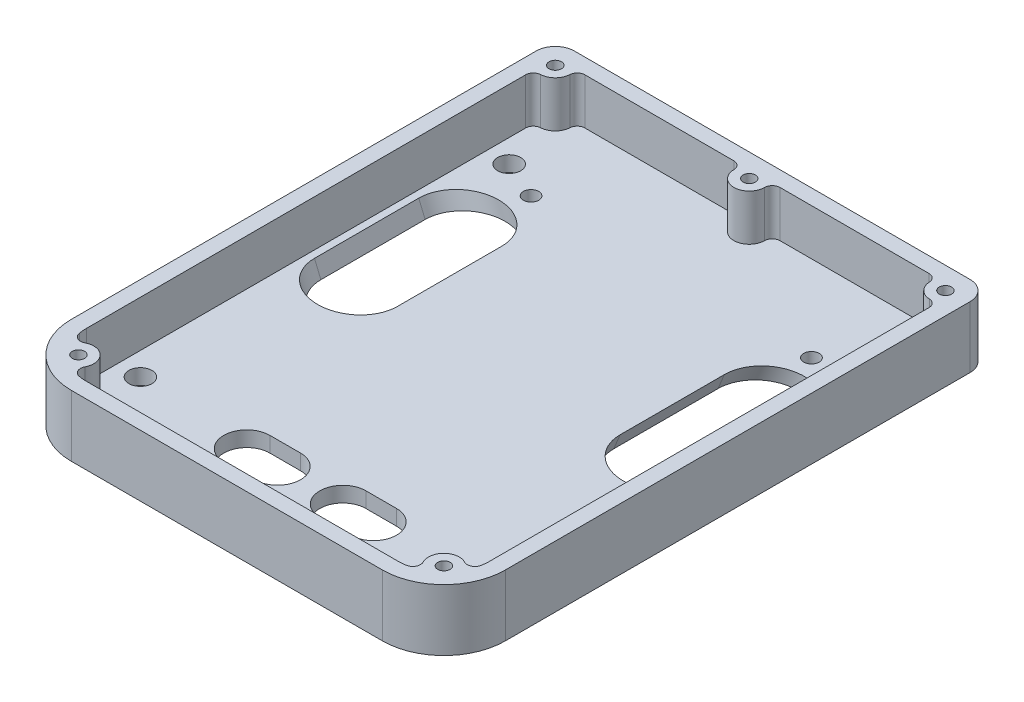
SolidWorks part; units mm, degrees
material "6061 Alloy"
ref_plane "Front Plane" through (0, 0, 0) normal (0, 0, 1) x (1, 0, 0)
ref_plane "Top Plane" through (0, 0, 0) normal (0, 1, 0) x (1, 0, 0)
ref_plane "Right Plane" through (0, 0, 0) normal (1, 0, 0) x (0, 0, -1)
sketch "Sketch1" plane through (0, 0, 0) normal (0, 1, 0) x (1, 0, 0)
  line L1 (-81.7563, 112.7125) -> (81.7563, 112.7125)
  line L2 (-89.6938, 104.775) -> (-89.6937, -87.3125)
  line L3 (-64.2937, -112.7125) -> (64.2938, -112.7125)
  line L4 (89.6938, 104.775) -> (89.6938, -87.3125)
  line L5 (-89.6938, 112.7125) -> (89.6938, -112.7125) construction
  line L6 (-89.6937, -112.7125) -> (89.6938, 112.7125) construction
  arc A0 (64.2938, -112.7125) -> (89.6938, -87.3125) centre (64.2938, -87.3125) ccw
  arc A1 (-89.6937, -87.3125) -> (-64.2937, -112.7125) centre (-64.2937, -87.3125) ccw
  arc A2 (81.7563, 112.7125) -> (89.6938, 104.775) centre (81.7563, 104.775) cw
  arc A3 (-81.7563, 112.7125) -> (-89.6938, 104.775) centre (-81.7563, 104.775) ccw
  point P0 (0, 0)
  dimension "D3" = 25.4
  dimension "D4" = 7.9375
  dimension "D1" = 225.425
  dimension "D2" = 179.3875
extrude "Boss-Extrude1" add sketch "Sketch1" along normal blind 6.35
sketch "Sketch2" plane through (0, 6.35, 0) normal (0, 1, 0) x (1, 0, 0)
  line L0 (81.7563, 106.3625) -> (-81.7563, 106.3625)
  line L1 (-83.3438, 104.775) -> (-83.3437, -87.3125)
  line L2 (-64.2937, -106.3625) -> (64.2938, -106.3625)
  line L3 (83.3438, -87.3125) -> (83.3438, 104.775)
  line L4 (89.6938, -87.3125) -> (89.6938, 104.775)
  line L5 (81.7563, 112.7125) -> (-81.7563, 112.7125)
  line L6 (-89.6938, 104.775) -> (-89.6937, -87.3125)
  line L7 (-64.2937, -112.7125) -> (64.2938, -112.7125)
  line L8 (89.6938, -87.3125) -> (89.6938, 104.775)
  line L9 (81.7563, 112.7125) -> (-81.7563, 112.7125)
  line L10 (-89.6938, 104.775) -> (-89.6937, -87.3125)
  line L11 (-64.2937, -112.7125) -> (64.2938, -112.7125)
  arc A0 (-81.7563, 106.3625) -> (-83.3438, 104.775) centre (-81.7563, 104.775) ccw
  arc A1 (-83.3437, -87.3125) -> (-64.2937, -106.3625) centre (-64.2937, -87.3125) ccw
  arc A2 (64.2938, -106.3625) -> (83.3438, -87.3125) centre (64.2938, -87.3125) ccw
  arc A3 (83.3438, 104.775) -> (81.7563, 106.3625) centre (81.7563, 104.775) ccw
  arc A4 (64.2938, -112.7125) -> (89.6938, -87.3125) centre (64.2938, -87.3125) ccw
  arc A5 (89.6938, 104.775) -> (81.7563, 112.7125) centre (81.7563, 104.775) ccw
  arc A6 (-81.7563, 112.7125) -> (-89.6938, 104.775) centre (-81.7563, 104.775) ccw
  arc A7 (-89.6937, -87.3125) -> (-64.2937, -112.7125) centre (-64.2937, -87.3125) ccw
  arc A8 (64.2938, -112.7125) -> (89.6938, -87.3125) centre (64.2938, -87.3125) ccw
  arc A9 (89.6938, 104.775) -> (81.7563, 112.7125) centre (81.7563, 104.775) ccw
  arc A10 (-81.7563, 112.7125) -> (-89.6938, 104.775) centre (-81.7563, 104.775) ccw
  arc A11 (-89.6937, -87.3125) -> (-64.2937, -112.7125) centre (-64.2937, -87.3125) ccw
  dimension "D1" = 0
  dimension "D2" = 6.35
extrude "Boss-Extrude2" add sketch "Sketch2" along normal blind 19.05
ref_plane "Plane1" through (-13.1353, 31.7115, 0) normal (-0.3827, 0.9239, 0) x (0, 0, 1)
ref_plane "Plane2" through (13.1353, 31.7115, 0) normal (0.3827, 0.9239, 0) x (0, 0, -1)
sketch "Sketch7" plane through (13.1353, 31.7115, 0) normal (0.3827, 0.9239, 0) x (0, 0, -1)
  line L0 (106.3625, -73.1029) -> (106.3625, 77.963) construction
  line L6 (46.9456, -40.0462) -> (3.8545, -40.0462)
  line L7 (3.8545, -71.7962) -> (46.9456, -71.7962)
  spline S4 degree 3 poles (46.9456, -40.0462) (78.6955, -40.0462) (78.6955, -71.7962) (46.9456, -71.7962) knots 0 0 0 0 1 1 1 1 weights 1 0.333333 0.333333 1
  spline S5 degree 3 poles (3.8545, -71.7962) (-27.8955, -71.7962) (-27.8955, -40.0462) (3.8545, -40.0462) knots 0 0 0 0 1 1 1 1 weights 1 0.333333 0.333333 1
  dimension "D1" = 43.0911
  dimension "D2" = 40.0462
  dimension "D3" = 31.75
  dimension "D4" = 59.4169
extrude "Cut-Extrude2" cut sketch "Sketch7" against normal blind 25.4 and the other way blind 6.35
sketch "Sketch8" plane through (0, 0, 0) normal (0, -1, 0) x (1, 0, 0)
  line L0 (13.4938, 78.2638) -> (26.1938, 78.2638) construction
  line L1 (13.4938, 87.7888) -> (26.1938, 87.7888)
  line L2 (13.4938, 68.7388) -> (26.1938, 68.7388)
  line L3 (89.6938, 87.3125) -> (89.6938, -104.775) construction
  line L4 (-64.2937, 112.7125) -> (64.2938, 112.7125) construction
  line L5 (-64.2937, 106.3625) -> (64.2938, 106.3625) construction
  line L8 (-64.2937, 106.3625) -> (64.2938, 106.3625) construction
  line L9 (0, 106.3625) -> (0, 51.3888) construction
  line L10 (-13.4938, 78.2638) -> (-26.1938, 78.2638) construction
  line L11 (-13.4938, 87.7888) -> (-26.1938, 87.7888)
  line L12 (-13.4938, 68.7388) -> (-26.1938, 68.7388)
  arc A0 (13.4938, 87.7888) -> (13.4938, 68.7388) centre (13.4938, 78.2638) ccw
  arc A1 (26.1938, 68.7388) -> (26.1938, 87.7888) centre (26.1938, 78.2638) ccw
  arc A4 (-13.4938, 87.7888) -> (-13.4938, 68.7388) centre (-13.4938, 78.2638) cw
  arc A5 (-26.1938, 68.7388) -> (-26.1938, 87.7888) centre (-26.1938, 78.2638) cw
  point P2 (19.8438, 78.2638)
  point P17 (-19.8438, 78.2638)
  dimension "D2" = 9.525
  dimension "D4" = 12.7
  dimension "D1" = 69.85
  dimension "D3" = 34.4487
extrude "Cut-Extrude3" cut sketch "Sketch8" against normal through all
sketch "Sketch9" plane through (0, 6.35, 0) normal (0, 1, 0) x (1, 0, 0)
  line L0 (-87.3689, 110.3877) -> (-80.6337, 103.6525) construction
  line L1 (-64.2937, -106.3625) -> (64.2938, -106.3625) construction
  line L5 (-64.2937, -106.3625) -> (64.2938, -106.3625) construction
  line L6 (-81.7563, 106.3625) -> (-71.1201, 106.3625)
  line L10 (81.7563, 106.3625) -> (-81.7563, 106.3625) construction
  line L11 (-83.3438, 104.775) -> (-83.3438, 94.1388)
  line L12 (-83.3438, 104.775) -> (-83.3437, -87.3125) construction
  line L14 (-82.2543, -105.273) -> (-64.2937, -87.3125) construction
  line L15 (-9.525, -106.3625) -> (9.525, -106.3625) construction
  line L16 (-133.9237, 0) -> (138.4201, 0) construction
  line L17 (0, 128.5214) -> (0, -157.9151) construction
  line L18 (-9.525, 106.3625) -> (9.525, 106.3625)
  line L19 (83.3438, 104.775) -> (83.3438, 94.1388)
  line L20 (81.7563, 106.3625) -> (71.1201, 106.3625)
  arc A4 (-83.0494, -90.6483) -> (-78.4553, -92.9075) centre (-79.9235, -90.0923) ccw
  circle A5 centre (-80.6337, 103.6525) radius 3.175 construction
  arc A7 (-69.8887, -101.4741) -> (-67.6295, -106.0682) centre (-67.0735, -102.9422) ccw
  arc A15 (-81.7563, 106.3625) -> (-83.3438, 104.775) centre (-81.7563, 104.775) ccw construction
  arc A24 (-81.7563, 112.7125) -> (-89.6938, 104.775) centre (-81.7563, 104.775) ccw construction
  arc A25 (-81.7563, 112.7125) -> (-89.6938, 104.775) centre (-81.7563, 104.775) ccw construction
  arc A26 (-80.3237, 97.31) -> (-74.2913, 103.3425) centre (-80.6337, 103.6525) ccw
  arc A27 (-81.7563, 106.3625) -> (-83.3438, 104.775) centre (-81.7563, 104.775) ccw
  arc A28 (-80.3237, 97.31) -> (-83.3438, 94.1388) centre (-80.1687, 94.1388) ccw
  arc A29 (-74.2913, 103.3425) -> (-71.1201, 106.3625) centre (-71.1201, 103.1875) cw
  circle A30 centre (-75.5191, -98.5378) radius 3.175 construction
  arc A31 (-83.3437, -87.3125) -> (-64.2937, -106.3625) centre (-64.2937, -87.3125) ccw construction
  arc A32 (-89.6937, -87.3125) -> (-64.2937, -112.7125) centre (-64.2937, -87.3125) ccw construction
  arc A33 (-89.6937, -87.3125) -> (-64.2937, -112.7125) centre (-64.2937, -87.3125) ccw construction
  arc A34 (-69.8887, -101.4741) -> (-78.4553, -92.9075) centre (-75.5191, -98.5378) ccw
  arc A35 (-83.0494, -90.6483) -> (-67.6295, -106.0682) centre (-64.2937, -87.3125) ccw
  arc A37 (-6.35, 103.1875) -> (-9.525, 106.3625) centre (-9.525, 103.1875) ccw
  arc A38 (6.35, 103.1875) -> (-6.35, 103.1875) centre (0, 103.1875) cw
  arc A39 (6.35, 103.1875) -> (9.525, 106.3625) centre (9.525, 103.1875) cw
  arc A40 (69.8887, -101.4741) -> (67.6295, -106.0682) centre (67.0735, -102.9422) cw
  arc A41 (83.0494, -90.6483) -> (67.6295, -106.0682) centre (64.2938, -87.3125) cw
  arc A42 (83.0494, -90.6483) -> (78.4553, -92.9075) centre (79.9235, -90.0923) cw
  arc A43 (69.8887, -101.4741) -> (78.4553, -92.9075) centre (75.5191, -98.5378) cw
  arc A44 (81.7563, 106.3625) -> (83.3438, 104.775) centre (81.7563, 104.775) cw
  arc A45 (80.3237, 97.31) -> (83.3438, 94.1388) centre (80.1687, 94.1388) cw
  arc A46 (80.3237, 97.31) -> (74.2913, 103.3425) centre (80.6337, 103.6525) cw
  arc A47 (74.2913, 103.3425) -> (71.1201, 106.3625) centre (71.1201, 103.1875) ccw
  circle A48 centre (0, 103.1875) radius 3.175 construction
  point P37 (-82.8788, 105.8975)
  dimension "D1" = 6.35
  dimension "D2" = 12.7
  dimension "D3" = 3.175
  dimension "D4" = 6.35
  dimension "D5" = 12.7
  dimension "D6" = 3.175
  dimension "D7" = 6.35
  dimension "D9" = 6.35
extrude "Boss-Extrude3" add sketch "Sketch9" along normal up to surface (19.05 mm away) up to face at (0, 25.4, -3.4615)
hole_wizard "1/4 (0.25) Diameter Hole1" positions "Sketch10" profile "Sketch11" hole size "1/4" standard "ANSI Inch" end condition through all
sketch "Sketch10" plane through (0, 6.35, 0) normal (0, 1, 0) x (1, 0, 0)
  point P0 (-57.9438, 70.9612)
  point P3 (-57.9437, -94.1387)
  point P6 (57.9438, -94.1387)
  point P9 (57.9437, 70.9612)
sketch "Sketch11" plane through (-57.9438, 6.35, -70.9612) normal (1, 0, 0) x (0, 0, 1)
  line L0 (0, 0) -> (0, 6.35)
  line L1 (0, 6.35) -> (3.175, 6.35)
  line L2 (3.175, 6.35) -> (3.175, 0)
  line L5 (3.175, 0) -> (0, 0)
  line L11 (0, -6.35) -> (0, 107.95) construction
  dimension "Thru Hole Dia." = 6.35
  dimension "Thru Hole Depth" = 6.35
hole_wizard "3/8 (0.375) Diameter Hole1" positions "Sketch12" profile "Sketch13" hole size "3/8" standard "ANSI Inch" end condition through all
sketch "Sketch12" plane through (0, 0, 0) normal (0, -1, 0) x (-1, 0, 0)
  point P0 (-73.8188, 77.7875)
  point P3 (73.8188, 77.7875)
  point P6 (73.8187, -74.6125)
  point P9 (-73.8188, -74.6125)
sketch "Sketch13" plane through (73.8188, 0, -77.7875) normal (1, 0, 0) x (0, 0, -1)
  line L0 (0, 0) -> (0, 25.4)
  line L1 (0, 25.4) -> (4.7625, 25.4)
  line L2 (4.7625, 25.4) -> (4.7625, 0)
  line L5 (4.7625, 0) -> (0, 0)
  line L11 (0, -6.35) -> (0, 107.95) construction
  dimension "Thru Hole Dia." = 9.525
  dimension "Thru Hole Depth" = 25.4
mirror "Mirror1" about plane through (0, 0, 0) normal (1, 0, 0) of "Cut-Extrude2"
hole_wizard "1/4-20 Tapped Hole1" positions "Sketch14" profile "Sketch15" tap size "1/4-20" standard "ANSI Inch"
sketch "Sketch14" plane through (0, 25.4, 0) normal (0, 1, 0) x (1, 0, 0)
  point P0 (-75.5191, -98.5378)
  point P3 (75.5191, -98.5378)
  point P6 (80.6337, 103.6525)
  point P9 (0, 103.1875)
  point P12 (-80.6337, 103.6525)
sketch "Sketch15" plane through (-75.5191, 25.4, 98.5378) normal (1, 0, 0) x (0, 0, 1)
  line L0 (0, 0) -> (0, 18.0438)
  line L1 (0, 18.0438) -> (2.5527, 16.51)
  line L2 (2.5527, 16.51) -> (2.5527, 0)
  line L5 (2.5527, 0) -> (0, 0)
  line L10 (0, 18.0438) -> (-2.5527, 16.51) construction
  line L11 (0, -6.35) -> (0, 107.95) construction
  dimension "Tap Drill Dia." = 5.1054
  dimension "Tap Drill Depth" = 16.51
  dimension "Drill Angle" = 118
cosmetic thread "Hole Thread1" parameters "D1"=12.7, "D2"=6.35
cosmetic thread "Hole Thread2" parameters "D1"=12.7, "D2"=6.35
cosmetic thread "Hole Thread3" parameters "D1"=12.7, "D2"=6.35
cosmetic thread "Hole Thread4" parameters "D1"=12.7, "D2"=6.35
cosmetic thread "Hole Thread5" parameters "D1"=12.7, "D2"=6.35
